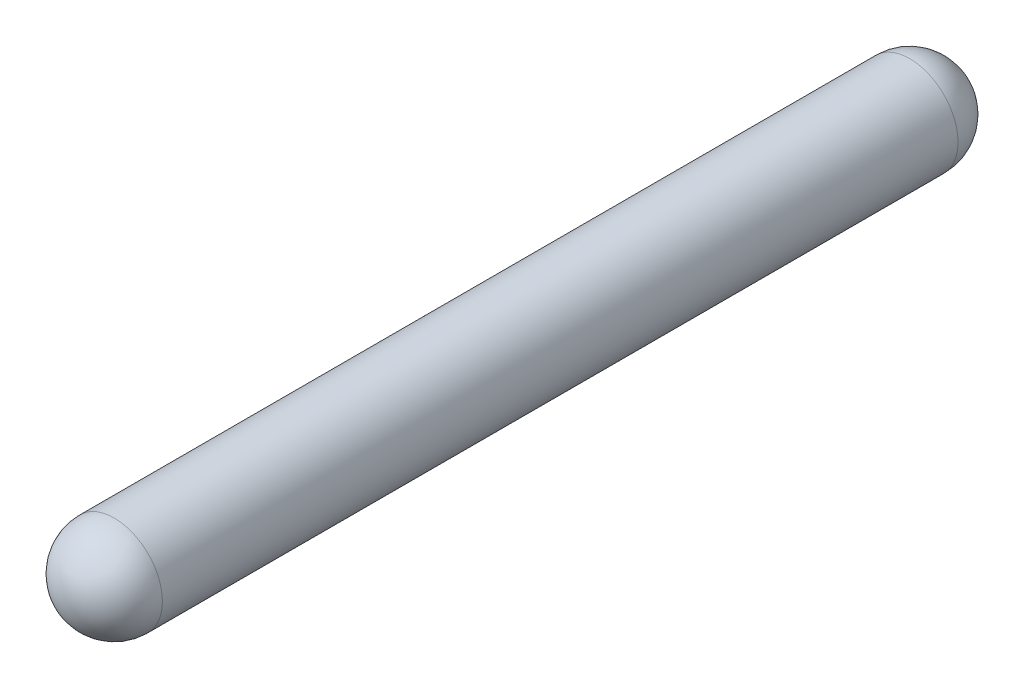
SolidWorks part; units mm, degrees
ref_plane "Front Plane" through (0, 0, 0) normal (0, 0, 1) x (1, 0, 0)
ref_plane "Top Plane" through (0, 0, 0) normal (0, 1, 0) x (1, 0, 0)
ref_plane "Right Plane" through (0, 0, 0) normal (1, 0, 0) x (0, 0, -1)
ref_plane "Plane1" through (0, 0, 0) normal (0, -1, 0) x (1, 0, 0)
sketch "Sketch1" plane through (0, 0, 0) normal (0, -1, 0) x (1, 0, 0)
  line L0 (0, 18.5) -> (0, -18.5)
  line L1 (2, -16.5) -> (2, 16.5)
  line L2 (0, 18.5) -> (0, -18.5) construction
  arc A0 (2, 16.5) -> (0, 18.5) centre (0, 16.5) ccw
  arc A1 (0, -18.5) -> (2, -16.5) centre (0, -16.5) ccw
revolve "Revolve1" add sketch "Sketch1" angle 360 about L2
